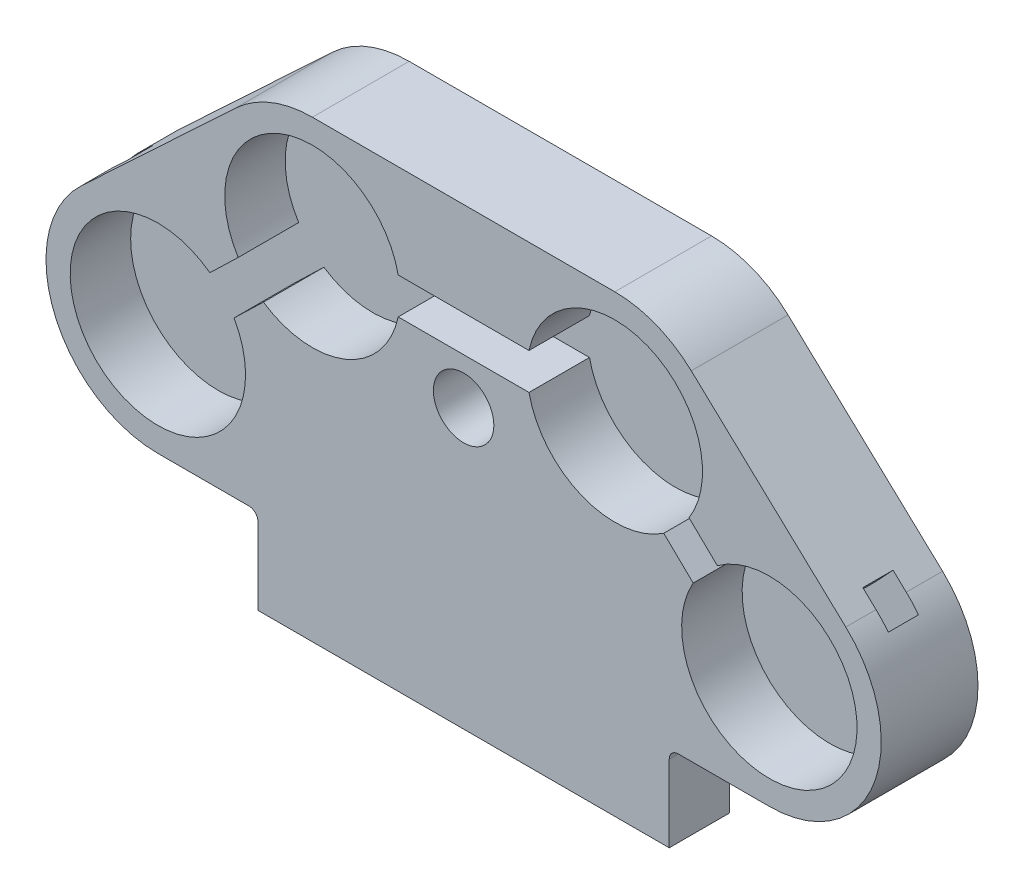
SolidWorks part; units mm, degrees
ref_plane "Front Plane" through (0, 0, 0) normal (0, 0, 1) x (1, 0, 0)
ref_plane "Top Plane" through (0, 0, 0) normal (0, 1, 0) x (1, 0, 0)
ref_plane "Right Plane" through (0, 0, 0) normal (1, 0, 0) x (0, 0, -1)
sketch "Sketch1" plane through (0, 0, 0) normal (0, 0, 1) x (1, 0, 0)
  line L0 (-11.9595, 12.7758) -> (-50.7466, -23.5332) construction
  line L1 (11.9595, 12.7758) -> (50.7466, -23.5332) construction
  line L2 (-11.9595, 12.7758) -> (11.9595, 12.7758) construction
  line L3 (-50.7466, -23.5332) -> (50.7466, -23.5332) construction
  line L4 (-17.5, -2) -> (17.5, -2) construction
  line L5 (0, 0) -> (0, -2) construction
  line L6 (-17.5, -2) -> (-17.5, 4) construction
  line L7 (-17.5, 4) -> (-20.5, 4) construction
  line L8 (-20.5, 4) -> (-20.5, -5) construction
  line L9 (-20.5, -5) -> (20.5, -5) construction
  line L10 (20.5, -5) -> (20.5, 4) construction
  line L11 (20.5, 4) -> (17.5, 4) construction
  line L12 (17.5, 4) -> (17.5, -2) construction
  line L13 (0, -2) -> (0, 40.1846) construction
  line L14 (-25.2758, 14.3506) -> (-12.5, 26.3101) construction
  line L15 (-31.5972, 21.1034) -> (-18.8215, 33.063)
  line L16 (-25.2758, 5.1006) -> (-17.75, 5.1006)
  line L17 (-17, 4.3506) -> (-17, -2)
  line L18 (-17, -2) -> (0, -2)
  line L19 (-12.5, 35.5601) -> (0, 35.5601)
  line L20 (0, 35.5601) -> (0, -2)
  circle A0 centre (0, 0) radius 17.5 construction
  circle A1 centre (-25.2758, 14.3506) radius 7.25
  circle A2 centre (-12.5, 26.3101) radius 7.25
  circle A3 centre (-12.5, 26.3101) radius 9.25 construction
  circle A4 centre (-25.2758, 14.3506) radius 9.25 construction
  arc A5 (-17.75, 5.1006) -> (-17, 4.3506) centre (-17.75, 4.3506) cw
  arc A6 (-18.8215, 33.063) -> (-12.5, 35.5601) centre (-12.5, 26.3101) cw
  arc A7 (-25.2758, 5.1006) -> (-31.5972, 21.1034) centre (-25.2758, 14.3506) cw
  dimension "D1" = 35
  dimension "D8" = 14.5
  dimension "D10" = 3
  dimension "D11" = 2
  dimension "D13" = 0.75
  dimension "D2" = 93.78
  dimension "D3" = 35
  dimension "2" = 2
  dimension "D4" = 6
  dimension "D5" = 3
  dimension "D6" = 3
  dimension "D7" = 3
  dimension "D9" = 25
  dimension "D12" = 0.5
extrude "Boss-Extrude1" add sketch "Sketch1" along normal blind 5 contours A7 L16 A5 L17 L18 L20 L19 A6 L15 A2 A1
mirror "Mirror1" about plane through (0, 0, 0) normal (1, 0, 0) of "Boss-Extrude1"
sketch "Sketch3" plane through (0, 0, 0) normal (0, 0, -1) x (-1, 0, 0)
  line L0 (31.5972, 21.1034) -> (18.8215, 33.063) construction
  line L1 (31.5972, 21.1034) -> (18.8215, 33.063)
  line L2 (12.5, 35.5601) -> (-12.5, 35.5601) construction
  line L3 (12.5, 35.5601) -> (-12.5, 35.5601)
  line L4 (-31.5972, 21.1034) -> (-18.8215, 33.063) construction
  line L5 (-31.5972, 21.1034) -> (-18.8215, 33.063)
  line L6 (-18.9543, 7.5977) -> (-6.1785, 19.5572)
  line L7 (18.9543, 7.5977) -> (6.1785, 19.5572)
  line L8 (-6.1785, 19.5572) -> (-1.3668, 24.0615)
  line L9 (1.3668, 24.0615) -> (6.1785, 19.5572)
  arc A0 (25.2758, 5.1006) -> (31.5972, 21.1034) centre (25.2758, 14.3506) ccw construction
  arc A1 (25.2758, 5.1006) -> (31.5972, 21.1034) centre (25.2758, 14.3506) ccw construction
  arc A2 (18.8215, 33.063) -> (12.5, 35.5601) centre (12.5, 26.3101) ccw construction
  arc A3 (18.8215, 33.063) -> (12.5, 35.5601) centre (12.5, 26.3101) ccw
  arc A4 (-12.5, 35.5601) -> (-18.8215, 33.063) centre (-12.5, 26.3101) ccw construction
  arc A5 (-12.5, 35.5601) -> (-18.8215, 33.063) centre (-12.5, 26.3101) ccw
  arc A6 (-31.5972, 21.1034) -> (-25.2758, 5.1006) centre (-25.2758, 14.3506) ccw construction
  arc A7 (-31.5972, 21.1034) -> (-25.2758, 5.1006) centre (-25.2758, 14.3506) ccw construction
  circle A8 centre (-25.2758, 14.3506) radius 9.25 construction
  circle A9 centre (-12.5, 26.3101) radius 9.25 construction
  circle A10 centre (12.5, 26.3101) radius 9.25 construction
  circle A11 centre (25.2758, 14.3506) radius 9.25 construction
  circle A12 centre (0, 12.957) radius 9.0409 construction
  arc A13 (-6.1785, 19.5572) -> (6.1785, 19.5572) centre (0, 12.957) cw construction
  arc A14 (-31.5972, 21.1034) -> (-18.9543, 7.5977) centre (-25.2758, 14.3506) ccw
  arc A15 (31.5972, 21.1034) -> (18.9543, 7.5977) centre (25.2758, 14.3506) cw
  arc A16 (-1.3668, 24.0615) -> (1.3668, 24.0615) centre (0, 22.6014) cw
  arc M9 (25.2758, 5.1006) -> (31.5972, 21.1034) centre (25.2758, 14.3506) ccw
  line M10 (31.5972, 21.1034) -> (18.8215, 33.063)
  arc M11 (18.8215, 33.063) -> (12.5, 35.5601) centre (12.5, 26.3101) ccw
  line M12 (12.5, 35.5601) -> (-12.5, 35.5601)
  arc M13 (-12.5, 35.5601) -> (-18.8215, 33.063) centre (-12.5, 26.3101) ccw
  line M14 (-18.8215, 33.063) -> (-31.5972, 21.1034)
  arc M15 (-31.5972, 21.1034) -> (-25.2758, 5.1006) centre (-25.2758, 14.3506) ccw
  circle M23 centre (12.5, 26.3101) radius 7.25
  circle M24 centre (25.2758, 14.3506) radius 7.25
  circle M25 centre (-12.5, 26.3101) radius 7.25
  circle M26 centre (-25.2758, 14.3506) radius 7.25
  dimension "D1" = 2
extrude "Boss-Extrude2" add sketch "Sketch3" along normal blind 3 contours A15 A14 L6 A13 L7 M9 M10 M11 M12 M13 M14 M15 M23 M25 M26 M24 | M26 | M25 | M23 | M24
sketch "Sketch4" plane through (0, 0, 0) normal (0, 0, 1) x (1, 0, 0)
  circle A0 centre (25.2758, 14.3506) radius 7.25 construction
  circle A1 centre (12.5, 26.3101) radius 7.25 construction
  circle A2 centre (-12.5, 26.3101) radius 7.25 construction
  circle A3 centre (-25.2758, 14.3506) radius 7.25 construction
  circle A4 centre (25.2758, 14.3506) radius 7.25
  circle A5 centre (12.5, 26.3101) radius 7.25
  circle A6 centre (-12.5, 26.3101) radius 7.25
  circle A7 centre (-25.2758, 14.3506) radius 7.25
extrude "Cut-Extrude1" [suppressed] cut sketch "Sketch4" against normal blind 1
sketch "Sketch5" plane through (0, 0, 5) normal (0, 0, 1) x (1, 0, 0)
  line L0 (-25.2758, 14.3506) -> (-12.5, 26.3101) construction
  line L1 (-12.8738, 28.0145) -> (-28.6641, 12.7641)
  line L2 (-28.6641, 12.7641) -> (-26.58, 10.6062)
  line L3 (-26.58, 10.6062) -> (-10.7897, 25.8567)
  line L4 (-10.7897, 25.8567) -> (-12.8738, 28.0145)
  line L5 (0, 0) -> (0, 28.253) construction
  line L6 (-12.5, 26.3101) -> (12.5, 26.3101) construction
  line L7 (-6.9065, 27.8101) -> (8.5226, 27.8101)
  line L8 (8.5226, 27.8101) -> (8.5226, 24.8101)
  line L9 (8.5226, 24.8101) -> (-6.9065, 24.8101)
  line L10 (-6.9065, 24.8101) -> (-6.9065, 27.8101)
  line L11 (26.58, 10.6062) -> (10.7897, 25.8567)
  line L12 (28.6641, 12.7641) -> (26.58, 10.6062)
  line L13 (12.8738, 28.0145) -> (28.6641, 12.7641)
  line L14 (10.7897, 25.8567) -> (12.8738, 28.0145)
  point P6 (-11.8318, 26.9356)
  point P16 (-6.9065, 26.3101)
  point P23 (-38.1252, 0)
  point P24 (-38.1252, 0)
  point P25 (-38.1252, 0)
  point P26 (0, 0)
  dimension "D1" = 3
  dimension "D2" = 3
extrude "Cut-Extrude2" cut sketch "Sketch5" against normal up to surface (5 mm away) up to face at (-18.0258, 14.3506, 0)
sketch "Sketch6" [suppressed] plane through (-25.9692, 27.7416, 0) normal (-0.6834, 0.73, 0) x (0.73, 0.6834, 0)
  line L0 (-16.9271, 1) -> (-1.556, 1) construction
  line L1 (-16.9271, 1) -> (-1.556, 1) construction
  line L2 (-9.1771, -5) -> (-9.1771, 4) construction
  line L3 (-7.6771, 1) -> (-10.6771, 1)
  line L4 (-7.6771, 1) -> (-7.6771, -1.5)
  line L5 (-7.6771, -1.5) -> (-10.6771, -1.5)
  line L6 (-10.6771, 1) -> (-10.6771, -1.5)
  point P8 (-9.1771, 1)
  dimension "D1" = 2.5
  dimension "D2" = 3
extrude "Cut-Extrude3" [suppressed] cut sketch "Sketch6" against normal blind 11
mirror "Mirror2" [suppressed] about plane through (0, 0, 0) normal (1, 0, 0)
sketch "Sketch7" plane through (-25.2858, 27.0116, 0) normal (-0.6834, 0.73, 0) x (0.73, 0.6834, 0)
  line L0 (-15.8952, 0) -> (-1.5171, 0) construction
  line L1 (-7.1452, 0) -> (-10.1452, 0)
  line L2 (-7.1452, 0) -> (-7.1452, -2.5)
  line L3 (-7.1452, -2.5) -> (-10.1452, -2.5)
  line L4 (-10.1452, 0) -> (-10.1452, -2.5)
  line L5 (-15.8952, 0) -> (-1.5171, 0) construction
  line L8 (-8.6452, -5) -> (-8.6452, 3) construction
  point P6 (-7.4615, 0)
  point P9 (-8.6452, -2.5)
  dimension "D1" = 3
  dimension "D2" = 2.5
extrude "Cut-Extrude4" cut sketch "Sketch7" against normal blind 10
mirror "Mirror3" about plane through (0, 0, 0) normal (1, 0, 0) of "Cut-Extrude4"
sketch "Sketch8" plane through (0, 0, 5) normal (0, 0, 1) x (1, 0, 0)
  circle A2 centre (0, 21) radius 3.75 construction
  circle A3 centre (0, 21) radius 2.5
  dimension "D1" = 7.5
  dimension "D2" = 5
  dimension "D3" = 21
extrude "Cut-Extrude5" cut sketch "Sketch8" against normal blind 10
